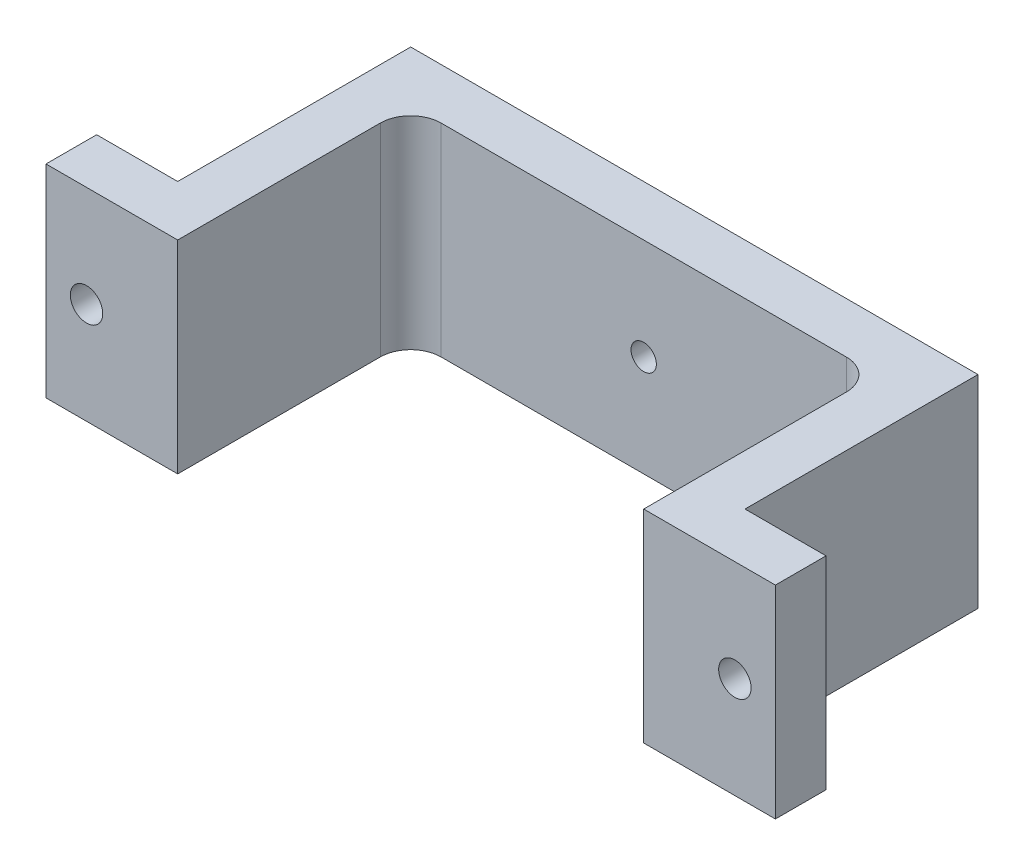
SolidWorks part; units mm, degrees
ref_plane "Спереди" through (0, 0, 0) normal (0, 0, 1) x (1, 0, 0)
ref_plane "Сверху" through (0, 0, 0) normal (0, 1, 0) x (1, 0, 0)
ref_plane "Справа" through (0, 0, 0) normal (1, 0, 0) x (0, 0, -1)
other "Configuration Table"
sketch "Sketch1" plane through (0, 0, 0) normal (0, 1, 0) x (1, 0, 0)
  line L0 (0, 16.1358) -> (0, -16.1358) construction
  line L2 (28, 12.5284) -> (-28, 12.5284)
  line L3 (-28, 12.5284) -> (-28, -10.4716)
  line L4 (-28, -10.4716) -> (-36, -10.4716)
  line L5 (-36, -10.4716) -> (-36, -15.4716)
  line L6 (-36, -15.4716) -> (-23, -15.4716)
  line L7 (-23, -15.4716) -> (-23, 7.5284)
  line L8 (-23, 7.5284) -> (23, 7.5284)
  line L10 (23, -15.4716) -> (23, 7.5284)
  line L11 (36, -15.4716) -> (23, -15.4716)
  line L12 (36, -10.4716) -> (36, -15.4716)
  line L13 (28, -10.4716) -> (36, -10.4716)
  line L14 (28, 12.5284) -> (28, -10.4716)
  point P4 (0, 0)
  point P12 (0, 7.5284)
  point P18 (0, 12.5284)
  dimension "D1" = 23
  dimension "D2" = 5
  dimension "D3" = 23
  dimension "D4" = 5
  dimension "D5" = 8
  dimension "D6" = 5
  dimension "D7" = 72
extrude "Boss-Extrude1" add sketch "Sketch1" along normal blind 20
fillet "Fillet1" radius 3 2 edges at (23, 10, -7.5284) (-23, 10, -7.5284)
sketch "Sketch3" plane through (0, 0, 15.4716) normal (0, 0, 1) x (1, 0, 0)
  line L0 (-36, 10) -> (36, 10) construction
  line L1 (-36, 20) -> (-36, 0) construction
  line L2 (36, 20) -> (36, 0) construction
  circle A0 centre (-32, 10) radius 1.6
  circle A1 centre (32, 10) radius 1.6
  dimension "D3" = 3.2
  dimension "D1" = 4
  dimension "D2" = 4
  dimension "D4" = 64
extrude "Cut-Extrude1" cut sketch "Sketch3" against normal up to next
sketch "Sketch4" plane through (0, 0, -12.5284) normal (0, 0, -1) x (-1, 0, 0)
  line L0 (-28, 20) -> (28, 0) construction
  line L1 (28, 0) -> (28, 20) construction
  line L2 (28, 20) -> (-28, 0) construction
  circle A0 centre (0, 10) radius 1.25
  dimension "D1" = 2.5
extrude "Cut-Extrude2" cut sketch "Sketch4" against normal up to next
